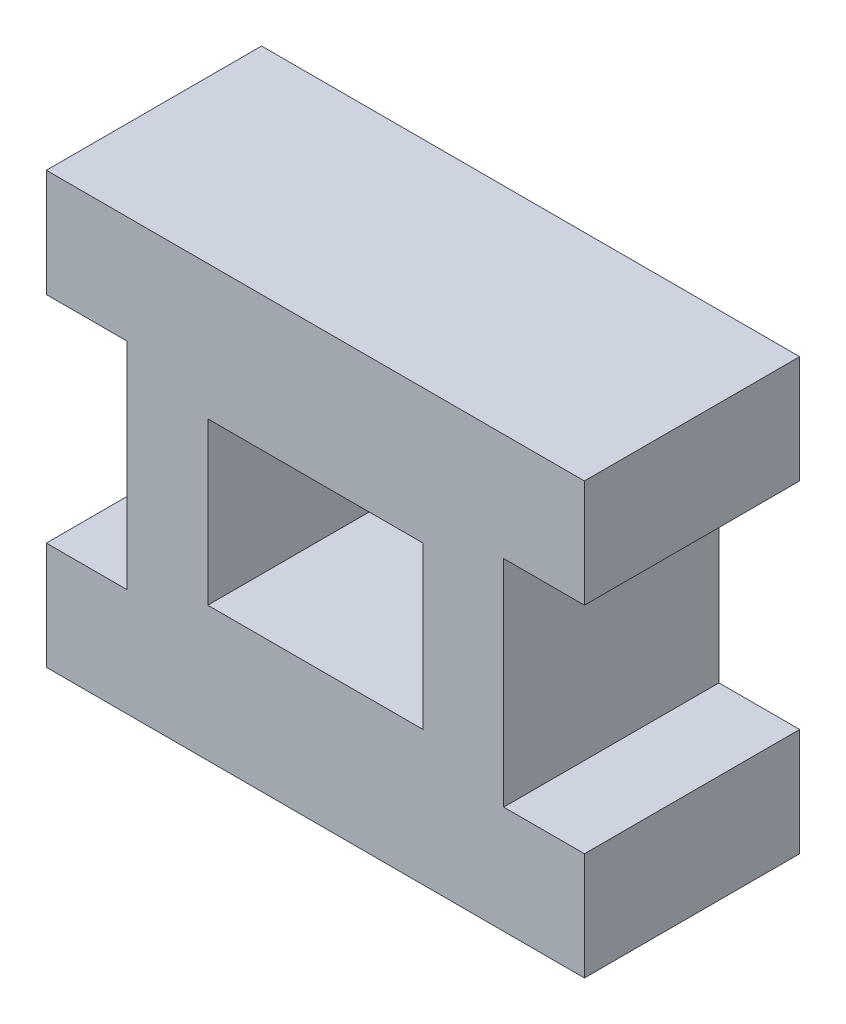
SolidWorks part; units mm, degrees
material "AISI 1020 Steel, Cold Rolled"
ref_plane "Front Plane" through (0, 0, 0) normal (0, 0, 1) x (1, 0, 0)
ref_plane "Top Plane" through (0, 0, 0) normal (0, 1, 0) x (1, 0, 0)
ref_plane "Right Plane" through (0, 0, 0) normal (1, 0, 0) x (0, 0, -1)
sketch "Sketch1" plane through (0, 0, 0) normal (0, 0, 1) x (1, 0, 0)
  line L0 (-34.0413, 29.3614) -> (65.9587, 29.3614)
  line L1 (-34.0413, 29.3614) -> (-34.0413, 9.3614)
  line L2 (65.9587, 29.3614) -> (65.9587, 9.3614)
  line L3 (-34.0413, 9.3614) -> (-19.0413, 9.3614)
  line L4 (65.9587, 9.3614) -> (50.9587, 9.3614)
  line L5 (-19.0413, 9.3614) -> (-19.0413, -30.6386)
  line L6 (50.9587, 9.3614) -> (50.9587, -30.6386)
  line L7 (-19.0413, -30.6386) -> (-34.0413, -30.6386)
  line L8 (50.9587, -30.6386) -> (65.9587, -30.6386)
  line L9 (-34.0413, -30.6386) -> (-34.0413, -50.6386)
  line L10 (65.9587, -30.6386) -> (65.9587, -50.6386)
  line L11 (-34.0413, -50.6386) -> (65.9587, -50.6386)
  line L12 (-4.0413, 4.3614) -> (-4.0413, -25.6386)
  line L13 (35.9587, 4.3614) -> (35.9587, -25.6386)
  line L14 (-4.0413, 4.3614) -> (35.9587, 4.3614)
  line L15 (-4.0413, -25.6386) -> (35.9587, -25.6386)
  point P16 (-4.0413, -10.6386)
  point P17 (-19.0413, -10.6386)
  point P18 (35.9587, -10.6386)
  point P19 (50.9587, -10.6386)
  dimension "D1" = 15
  dimension "D2" = 100
  dimension "D3" = 40
  dimension "D4" = 40
  dimension "D5" = 15
  dimension "D6" = 15
  dimension "D7" = 15
  dimension "D8" = 20
  dimension "D9" = 20
  dimension "D10" = 20
  dimension "D11" = 20
  dimension "D12" = 100
  dimension "D13" = 15
  dimension "D14" = 15
  dimension "D15" = 40
  dimension "D16" = 30
extrude "Boss-Extrude1" add sketch "Sketch1" along normal blind 40
